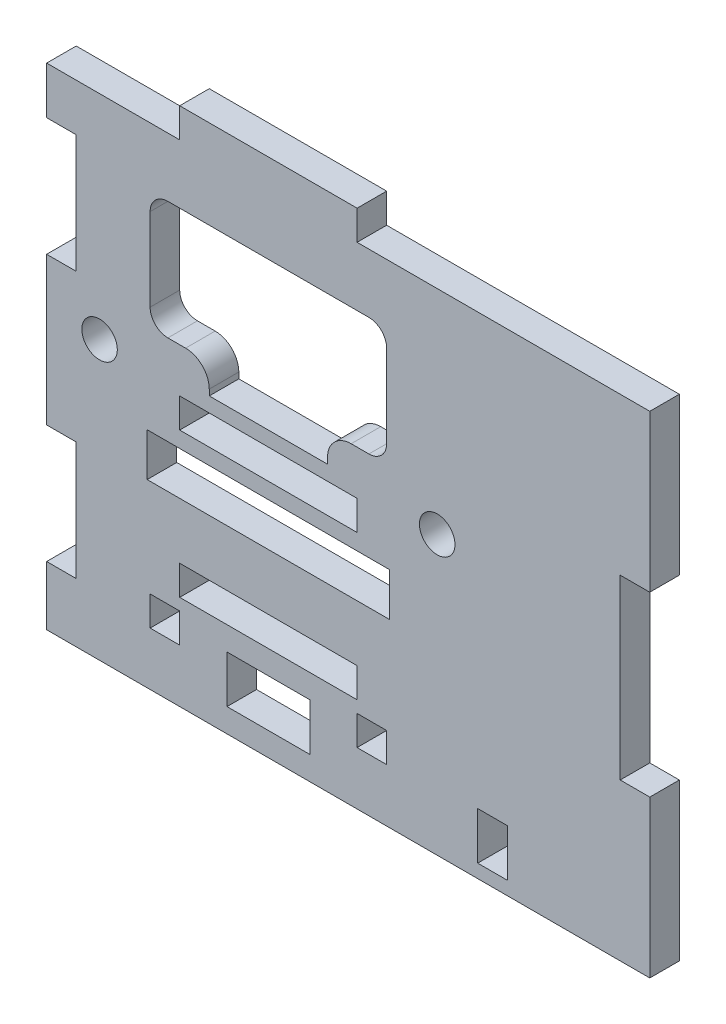
SolidWorks part; units mm, degrees
ref_plane "前视基准面" through (0, 0, 0) normal (0, 0, 1) x (1, 0, 0)
ref_plane "上视基准面" through (0, 0, 0) normal (0, 1, 0) x (1, 0, 0)
ref_plane "右视基准面" through (0, 0, 0) normal (1, 0, 0) x (0, 0, -1)
sketch "草图1" plane through (0, 0, 0) normal (0, 0, 1) x (1, 0, 0)
  line L0 (-77.5, 0) -> (24.5, 0)
  line L1 (-77.5, 0) -> (-77.5, 10)
  line L2 (-77.5, 83) -> (-55, 83)
  line L3 (-25, 83) -> (24.5, 83)
  line L4 (-57, 53) -> (-54, 53)
  line L5 (24.5, 26.5) -> (24.5, 0)
  line L6 (-55, 83) -> (-55, 88)
  line L7 (-55, 88) -> (-25, 88)
  line L8 (-25, 83) -> (-25, 88)
  line L9 (24.5, 83) -> (24.5, 56.5)
  line L10 (24.5, 56.5) -> (19.5, 56.5)
  line L11 (-60, 56) -> (-60, 70)
  line L12 (-55, 45.5) -> (-25, 45.5)
  line L13 (-55, 45.5) -> (-55, 40.5)
  line L14 (-55, 40.5) -> (-25, 40.5)
  line L15 (-25, 45.5) -> (-25, 40.5)
  line L16 (-55, 45.5) -> (-25, 40.5) construction
  line L17 (-55, 40.5) -> (-25, 45.5) construction
  line L18 (-57, 73) -> (-23, 73)
  line L19 (-20, 70) -> (-20, 56)
  line L20 (-26, 53) -> (-23, 53)
  line L21 (-77.5, 75) -> (-77.5, 83)
  line L22 (24.5, 26.5) -> (19.5, 26.5)
  line L23 (19.5, 56.5) -> (19.5, 26.5)
  line L24 (-77.5, 75) -> (-72.5, 75)
  line L25 (-77.5, 30) -> (-77.5, 55)
  line L26 (-77.5, 55) -> (-72.5, 55)
  line L27 (-72.5, 75) -> (-72.5, 55)
  line L28 (-77.5, 10) -> (-72.5, 10)
  line L29 (0.4, 82.3551) -> (0.4, -15.592) construction
  line L30 (-55, 16) -> (-50, 16)
  line L31 (-50, 49) -> (-50, 48)
  line L32 (-50, 48) -> (-30, 48)
  line L33 (-30, 49) -> (-30, 48)
  line L34 (-55, 21) -> (-25, 21)
  line L35 (-55, 21) -> (-55, 16)
  line L36 (-50, 16) -> (-30, 16)
  line L37 (-25, 21) -> (-25, 16)
  line L38 (-30, 16) -> (-25, 16)
  line L39 (-61.6343, 14) -> (-21.8599, 14) construction
  line L40 (-77.5, 30) -> (-72.5, 30)
  line L41 (-55, 14) -> (-60, 14)
  line L42 (-55, 14) -> (-55, 9)
  line L43 (-55, 9) -> (-60, 9)
  line L44 (-60, 14) -> (-60, 9)
  line L45 (-25, 14) -> (-20, 14)
  line L46 (-47, 12) -> (-33, 12)
  line L47 (-47, 12) -> (-47, 4)
  line L48 (-47, 4) -> (-33, 4)
  line L49 (-33, 12) -> (-33, 4)
  line L50 (-25, 14) -> (-25, 9)
  line L51 (-25, 9) -> (-20, 9)
  line L52 (-20, 14) -> (-20, 9)
  line L53 (-60.5, 30.5) -> (-19.5, 30.5)
  line L54 (-60.5, 30.5) -> (-60.5, 37.8)
  line L55 (-60.5, 37.8) -> (-19.5, 37.8)
  line L56 (-19.5, 30.5) -> (-19.5, 37.8)
  line L57 (-72.5, 10) -> (-72.5, 30)
  line L59 (0.4, 10.27) -> (-4.6, 10.27)
  line L60 (0.4, 10.27) -> (0.4, 2.27)
  line L61 (0.4, 2.27) -> (-4.6, 2.27)
  line L62 (-4.6, 10.27) -> (-4.6, 2.27)
  circle A0 centre (-68.55, 47) radius 3
  circle A1 centre (-11.45, 47) radius 3
  arc A2 (-26, 53) -> (-30, 49) centre (-26, 49) ccw
  arc A3 (-54, 53) -> (-50, 49) centre (-54, 49) cw
  arc A4 (-60, 70) -> (-57, 73) centre (-57, 70) cw
  arc A5 (-23, 73) -> (-20, 70) centre (-23, 70) cw
  arc A6 (-20, 56) -> (-23, 53) centre (-23, 56) cw
  arc A7 (-60, 56) -> (-57, 53) centre (-57, 56) ccw
  point P0 (-55, 11.5)
  point P19 (-40, 43)
  point P48 (-50, 53)
  point P75 (-60, 73)
  point P78 (-20, 73)
  point P81 (-20, 53)
  point P84 (-60, 53)
  dimension "D10" = 20
  dimension "D26" = 4
  dimension "D27" = 16
  dimension "D51" = 3
  dimension "D4" = 102
  dimension "D5" = 30
  dimension "D6" = 5.5
  dimension "D7" = 83
  dimension "D8" = 2.5
  dimension "D9" = 40
  dimension "D11" = 5
  dimension "D12" = 20
  dimension "D13" = 17.5
  dimension "D14" = 8.95
  dimension "D15" = 83
  dimension "D16" = 17
  dimension "D17" = 57.1
  dimension "D18" = 22.5
  dimension "D19" = 17.5
  dimension "D20" = 5
  dimension "D21" = 5
  dimension "D22" = 5
  dimension "D23" = 5
  dimension "D24" = 8
  dimension "D25" = 5
  dimension "D28" = 5
  dimension "D29" = 30.5
  dimension "D30" = 14
  dimension "D31" = 8
  dimension "D32" = 47
  dimension "D33" = 2
  dimension "D34" = 41
  dimension "D35" = 5
  dimension "D36" = 30
  dimension "D37" = 22.5
  dimension "D38" = 26.5
  dimension "D39" = 30
  dimension "D40" = 5
  dimension "D41" = 10
  dimension "D42" = 20
  dimension "D43" = 20
  dimension "D44" = 8
  dimension "D45" = 4
  dimension "D46" = 40.5
  dimension "D47" = 8
  dimension "D48" = 5
  dimension "D49" = 2.27
  dimension "D50" = 19.1
  dimension "D52" = 5
extrude "凸台-拉伸1" add sketch "草图1" along normal blind 5
